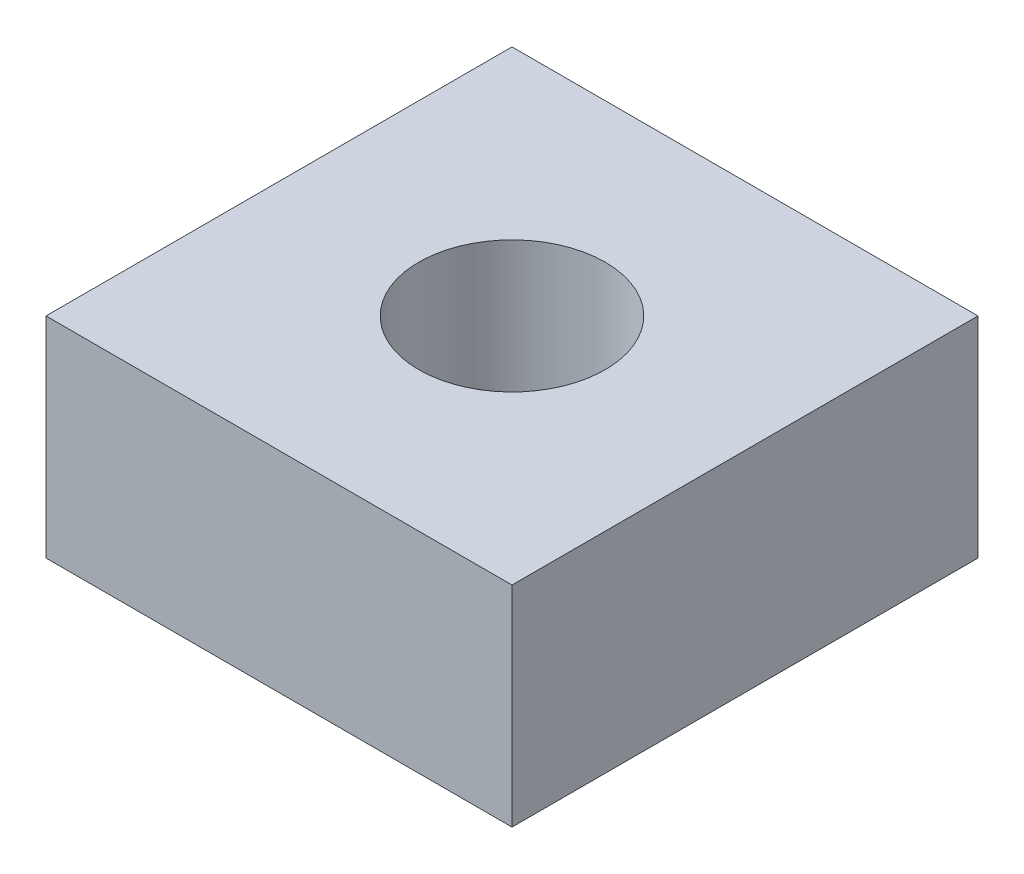
SolidWorks part; units mm, degrees
ref_plane "Front Plane" through (0, 0, 0) normal (0, 0, 1) x (1, 0, 0)
ref_plane "Top Plane" through (0, 0, 0) normal (0, 1, 0) x (1, 0, 0)
ref_plane "Right Plane" through (0, 0, 0) normal (1, 0, 0) x (0, 0, -1)
sketch "Sketch1" plane through (0, 0, 0) normal (0, 1, 0) x (1, 0, 0)
  line L1 (5, -5) -> (-5, -5)
  line L2 (5, -5) -> (5, 5)
  line L3 (5, 5) -> (-5, 5)
  line L4 (-5, -5) -> (-5, 5)
  line L5 (5, -5) -> (-5, 5) construction
  line L6 (5, 5) -> (-5, -5) construction
  circle A0 centre (0, 0) radius 2
  point P0 (0, 0)
  dimension "D1" = 10
  dimension "D2" = 10
extrude "Boss-Extrude1" add sketch "Sketch1" along normal blind 4.5
